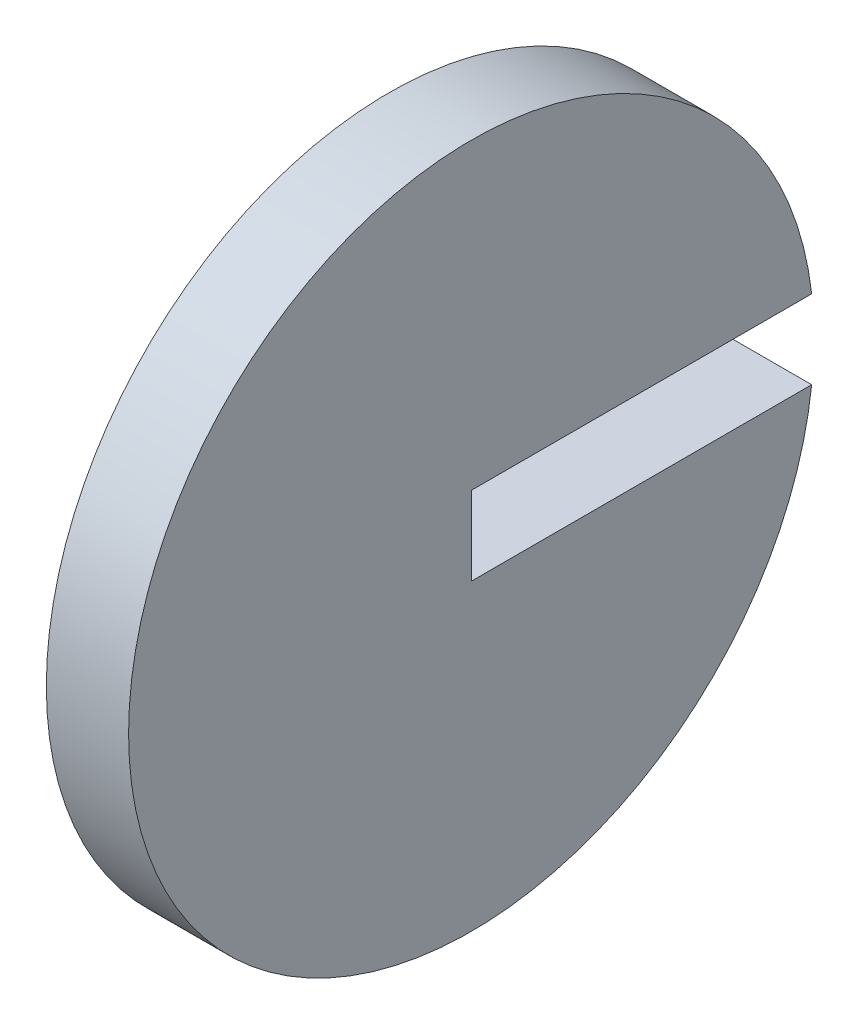
SolidWorks part; units mm, degrees
ref_plane "Front Plane" through (0, 0, 0) normal (0, 0, 1) x (1, 0, 0)
ref_plane "Top Plane" through (0, 0, 0) normal (0, 1, 0) x (1, 0, 0)
ref_plane "Right Plane" through (0, 0, 0) normal (1, 0, 0) x (0, 0, -1)
sketch "Sketch1" plane through (0, 0, 0) normal (1, 0, 0) x (0, 0, -1)
  circle A0 centre (0, 0) radius 12.5
  dimension "D1" = 25
extrude "Boss-Extrude1" add sketch "Sketch1" along normal blind 3
sketch "Sketch2" plane through (3, 0, 0) normal (1, 0, 0) x (0, 0, -1)
  line L0 (-20.0093, 0) -> (20.0093, 0) construction
  line L2 (0, -1.435) -> (25, -1.435)
  line L3 (0, -1.435) -> (0, 1.435)
  line L4 (0, 1.435) -> (25, 1.435)
  line L5 (25, -1.435) -> (25, 1.435)
  line L6 (0, -1.435) -> (25, 1.435) construction
  line L7 (0, 1.435) -> (25, -1.435) construction
  circle A0 centre (0, 0) radius 12.5 construction
  point P0 (12.5, 0)
  point P5 (0, 0)
  dimension "D1" = 2.87
  dimension "D2" = 25
extrude "Cut-Extrude1" cut sketch "Sketch2" against normal blind 3
